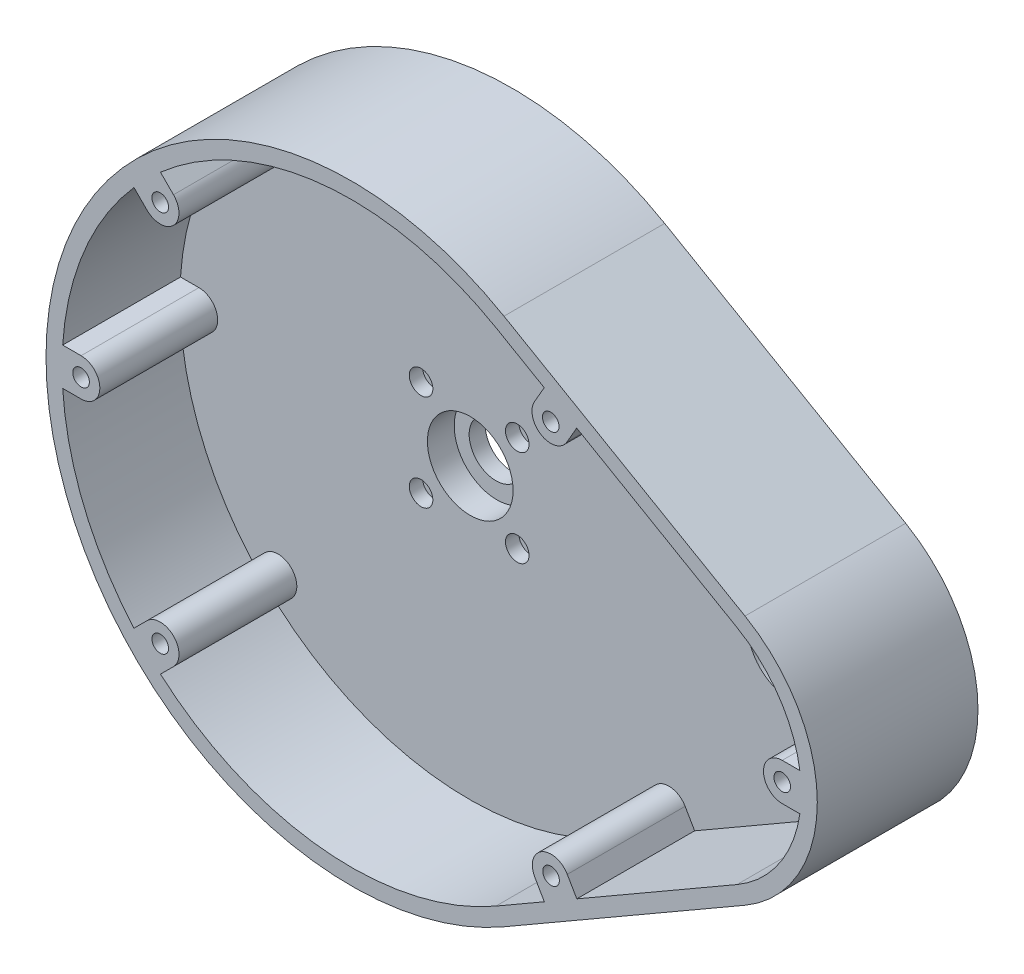
SolidWorks part; units mm, degrees
ref_plane "Front Plane" through (0, 0, 0) normal (0, 0, 1) x (1, 0, 0)
ref_plane "Top Plane" through (0, 0, 0) normal (0, 1, 0) x (1, 0, 0)
ref_plane "Right Plane" through (0, 0, 0) normal (1, 0, 0) x (0, 0, -1)
sketch "Sketch1" plane through (0, 0, 0) normal (0, 0, 1) x (1, 0, 0)
  line L0 (-30, 0) -> (30, 0) construction
  line L3 (-1.5, 49.3634) -> (43.5, 23.3827)
  line L4 (-1.5, -49.3634) -> (43.5, -23.3827)
  circle A0 centre (-30, 0) radius 57 construction
  circle A1 centre (30, 0) radius 27 construction
  circle A4 centre (-30, 0) radius 46.5 construction
  circle A5 centre (30, 0) radius 16.5 construction
  arc A6 (-1.5, 49.3634) -> (-1.5, -49.3634) centre (-30, 0) ccw
  arc A7 (43.5, 23.3827) -> (43.5, -23.3827) centre (30, 0) cw
  point P4 (0, 0)
extrude "Boss-Extrude1" add sketch "Sketch1" along normal blind 30 contours L4 A7 L3 A6
sketch "Sketch3" plane through (0, 0, 30) normal (0, 0, 1) x (1, 0, 0)
  line L7 (-82, 0) -> (-80.45, 0) construction
  line L8 (50.45, 3.5259) -> (53.7396, 3.5259)
  line L9 (50.45, -3.4741) -> (53.7472, -3.4741)
  line L10 (-7.1426, 46.707) -> (40.9581, 19.0767) construction
  line L11 (-4, -45.0333) -> (41, -19.0526) construction
  line L29 (-80.45, 3.5) -> (-83.8865, 3.5)
  line L30 (-80.45, -3.5) -> (-83.8865, -3.5)
  line L34 (-85.2387, -55.2387) -> (25.2387, 55.2387) construction
  line L36 (27.2243, -57.2243) -> (-87.2243, 57.2243) construction
  line L37 (-66.7696, 36.7696) -> (-65.6735, 35.6735) construction
  line L38 (-68.1484, 33.1987) -> (-63.1987, 38.1484) construction
  line L39 (-63.1987, 38.1484) -> (-65.6286, 40.5784)
  line L40 (-68.1484, 33.1987) -> (-70.5784, 35.6286)
  line L41 (-66.7696, -36.7696) -> (-65.6735, -35.6735) construction
  line L42 (-68.1484, -33.1987) -> (-63.1987, -38.1484) construction
  line L43 (-68.1484, -33.1987) -> (-70.5784, -35.6286)
  line L44 (-63.1987, -38.1484) -> (-65.6286, -40.5784)
  line L45 (8.0055, 38.0055) -> (7.2334, 36.6615) construction
  line L46 (4.1985, 38.4048) -> (10.2684, 34.9181) construction
  line L47 (4.1985, 38.4048) -> (6.0191, 41.5582)
  line L48 (10.2684, 34.9181) -> (12.0813, 38.0582)
  line L49 (8.0666, -38.0666) -> (7.2916, -36.7243) construction
  line L50 (4.2606, -38.4743) -> (10.3227, -34.9743) construction
  line L51 (10.3227, -34.9743) -> (12.0977, -38.0487)
  line L52 (4.2606, -38.4743) -> (6.0356, -41.5487)
  line L53 (42, -20.7846) -> (12.0977, -38.0487)
  line L54 (12.0813, 38.0582) -> (42, 20.7846)
  line L55 (-3, 46.7654) -> (6.0191, 41.5582)
  line L56 (-3, -46.7654) -> (6.0356, -41.5487)
  circle A6 centre (-30, 0) radius 52 construction
  circle A7 centre (30, 0) radius 22 construction
  arc A12 (50.45, -3.4741) -> (50.45, 3.5259) centre (50.45, 0.0259) cw
  circle A13 centre (50.45, 0.0259) radius 1.55
  arc A22 (42, 20.7846) -> (53.7396, 3.5259) centre (30, 0) cw
  arc A23 (53.7472, -3.4741) -> (42, -20.7846) centre (30, 0) cw
  arc A30 (-65.6286, 40.5784) -> (-3, 46.7654) centre (-30, 0) cw
  arc A32 (-70.5784, 35.6286) -> (-83.8865, 3.5) centre (-30, 0) ccw
  circle A41 centre (-80.45, 0) radius 1.55
  arc A42 (-80.45, 3.5) -> (-80.45, -3.5) centre (-80.45, 0) cw
  circle A44 centre (-65.6735, 35.6735) radius 1.55
  arc A45 (-63.1987, 38.1484) -> (-68.1484, 33.1987) centre (-65.6735, 35.6735) cw
  circle A46 centre (-65.6735, -35.6735) radius 1.55
  arc A47 (-68.1484, -33.1987) -> (-63.1987, -38.1484) centre (-65.6735, -35.6735) cw
  circle A48 centre (7.2334, 36.6615) radius 1.55
  arc A49 (4.1985, 38.4048) -> (10.2684, 34.9181) centre (7.2334, 36.6615) ccw
  circle A51 centre (7.2916, -36.7243) radius 1.55
  arc A52 (4.2606, -38.4743) -> (10.3227, -34.9743) centre (7.2916, -36.7243) cw
  arc A53 (-83.8865, -3.5) -> (-70.5784, -35.6286) centre (-30, 0) ccw
  arc A54 (-65.6286, -40.5784) -> (-3, -46.7654) centre (-30, 0) ccw
  point P1 (0, 0)
  point P10 (-30, 0)
  point P12 (0, 0)
  point P20 (-30, 0)
  point P32 (-30, 0)
  point P35 (-30, 0)
  point P37 (-30, 0)
  point P39 (-30, 0)
  point P45 (-65.6735, 35.6735)
  point P56 (-65.6735, -35.6735)
  point P59 (-30, 0)
  point P63 (0, 0)
  point P64 (0, 0)
  point P65 (0, 0)
  point P68 (0, 0)
  point P72 (7.2334, 36.6615)
  point P85 (7.2916, -36.7243)
extrude "Cut-Extrude1" cut sketch "Sketch3" against normal blind 22
sketch "Sketch5" plane through (0, 0, 0) normal (0, 0, -1) x (-1, 0, 0)
  circle A12 centre (65.6735, 35.6735) radius 1.55
  circle A13 centre (80.45, 0) radius 1.55
  circle A14 centre (-7.2334, 36.6615) radius 1.55
  circle A15 centre (-50.45, 0.0259) radius 1.55
  circle A16 centre (-7.2916, -36.7243) radius 1.55
  circle A17 centre (65.6735, -35.6735) radius 1.55
extrude "Cut-Extrude2" cut sketch "Sketch5" against normal blind 30
sketch "Sketch6" plane through (0, 0, 0) normal (0, 0, -1) x (-1, 0, 0)
  circle A12 centre (-50.45, 0.0259) radius 3
  circle A13 centre (-7.2916, -36.7243) radius 3
  circle A14 centre (65.6735, -35.6735) radius 3
  circle A15 centre (80.45, 0) radius 3
  circle A16 centre (65.6735, 35.6735) radius 3
  circle A17 centre (-7.2334, 36.6615) radius 3
extrude "Cut-Extrude3" cut sketch "Sketch6" against normal blind 5
sketch "Sketch7" plane through (0, 0, 8) normal (0, 0, 1) x (1, 0, 0)
  circle A4 centre (-29.7959, 0) radius 8
  circle A6 centre (30, 0) radius 8
extrude "Cut-Extrude10" cut sketch "Sketch7" against normal blind 5
sketch "Sketch8" plane through (0, 0, 8) normal (0, 0, 1) x (1, 0, 0)
  line L0 (-30, 0) -> (-38.9803, 8.9803) construction
  circle A0 centre (-30, 0) radius 5
  circle A1 centre (-30, 0) radius 12.7 construction
  circle A2 centre (-38.9803, 8.9803) radius 1.05
  circle A3 centre (-21.0197, 8.9803) radius 1.05
  circle A4 centre (-21.0197, -8.9803) radius 1.05
  circle A5 centre (-38.9803, -8.9803) radius 1.05
  point P7 (-30, 0)
  point P10 (-30, 0)
  point P17 (-30, 0)
  dimension "D1" = 4
extrude "Cut-Extrude7" cut sketch "Sketch8" against normal blind 8
sketch "Sketch9" plane through (0, 0, 8) normal (0, 0, 1) x (1, 0, 0)
  circle A0 centre (-38.9803, 8.9803) radius 2.2
  circle A1 centre (-21.0197, 8.9803) radius 2.2
  circle A2 centre (-21.0197, -8.9803) radius 2.2
  circle A3 centre (-38.9803, -8.9803) radius 2.2
  point P12 (-30, 0)
  dimension "D1" = 4
extrude "Cut-Extrude8" cut sketch "Sketch9" against normal blind 2.5
sketch "Sketch10" plane through (0, 0, 30) normal (0, 0, 1) x (1, 0, 0)
  line L0 (-3.0003, 46.7655) -> (42, 20.7849)
  line L2 (-3.0003, -46.7655) -> (42, -20.7849)
  line L3 (-4, 45.0333) -> (41, 19.0526)
  line L4 (-4, -45.0333) -> (41, -19.0526)
  circle A0 centre (-30, 0) radius 54 construction
  circle A1 centre (30, 0) radius 24.0003 construction
  arc A2 (-3.0003, 46.7655) -> (-3.0003, -46.7655) centre (-30, 0) ccw
  arc A3 (42, 20.7849) -> (42, -20.7849) centre (30, 0) cw
  circle A4 centre (-30, 0) radius 52 construction
  circle A5 centre (30, 0) radius 22 construction
  arc A6 (41, 19.0526) -> (41, -19.0526) centre (30, 0) cw
  arc A7 (-4, 45.0333) -> (-4, -45.0333) centre (-30, 0) ccw
  point P17 (0, 0)
